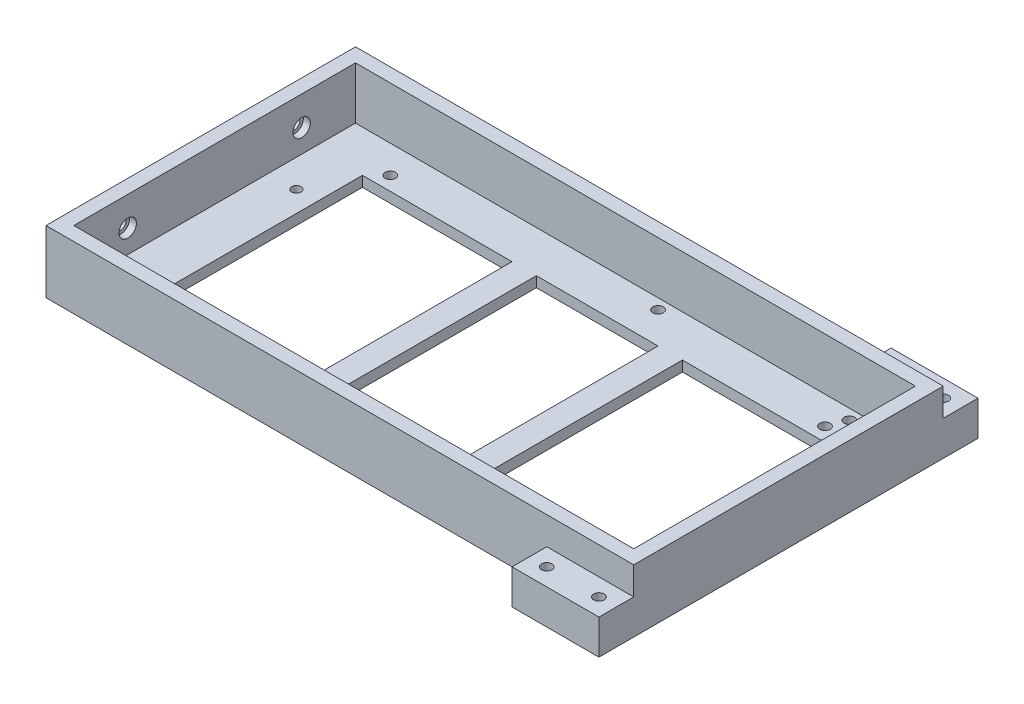
SolidWorks part; units mm, degrees
ref_plane "Front Plane" through (0, 0, 0) normal (0, 0, 1) x (1, 0, 0)
ref_plane "Top Plane" through (0, 0, 0) normal (0, 1, 0) x (1, 0, 0)
ref_plane "Right Plane" through (0, 0, 0) normal (1, 0, 0) x (0, 0, -1)
sketch "Sketch1" plane through (0, 0, 0) normal (0, 1, 0) x (1, 0, 0)
  line L1 (-80.5, -40.5) -> (80.5, -40.5)
  line L2 (-80.5, -40.5) -> (-80.5, 40.5)
  line L3 (-80.5, 40.5) -> (80.5, 40.5)
  line L4 (80.5, -40.5) -> (80.5, 40.5)
  line L5 (-80.5, -40.5) -> (80.5, 40.5) construction
  line L6 (-80.5, 40.5) -> (80.5, -40.5) construction
  line L7 (-84.5, -44.5) -> (84.5, -44.5)
  line L8 (-84.5, -44.5) -> (-84.5, 44.5)
  line L9 (-84.5, 44.5) -> (84.5, 44.5)
  line L10 (84.5, -44.5) -> (84.5, 44.5)
  line L11 (-84.5, -44.5) -> (84.5, 44.5) construction
  line L12 (-84.5, 44.5) -> (84.5, -44.5) construction
  point P0 (0, 0)
  point P6 (0, 0)
  dimension "D1" = 161
  dimension "D2" = 81
  dimension "D3" = 4
  dimension "D4" = 4
extrude "Boss-Extrude1" add sketch "Sketch1" along normal blind 15
sketch "Sketch2" plane through (0, 0, 0) normal (0, -1, 0) x (-1, 0, 0)
  line L0 (80.5, -40.5) -> (-80.5, -40.5) construction
  line L1 (84.5, 44.5) -> (-84.5, 44.5)
  line L2 (84.5, 44.5) -> (84.5, -44.5)
  line L3 (84.5, -44.5) -> (-84.5, -44.5)
  line L4 (-84.5, 44.5) -> (-84.5, -44.5)
  line L5 (84.5, 44.5) -> (-84.5, -44.5) construction
  line L6 (84.5, -44.5) -> (-84.5, 44.5) construction
  line L7 (66.5, 28.5) -> (23.5, 28.5)
  line L8 (66.5, 28.5) -> (66.5, -28.5)
  line L9 (66.5, -28.5) -> (23.5, -28.5)
  line L10 (-66.5, 28.5) -> (-66.5, -28.5)
  line L11 (66.5, 28.5) -> (-66.5, -28.5) construction
  line L12 (66.5, -28.5) -> (-66.5, 28.5) construction
  line L14 (-80.5, -40.5) -> (-80.5, 40.5) construction
  line L15 (-18.5, -28.5) -> (-18.5, 28.5)
  line L16 (-25.5, 28.5) -> (-25.5, -28.5)
  line L17 (-25.5, -28.5) -> (-66.5, -28.5)
  line L18 (-25.5, 28.5) -> (-66.5, 28.5)
  line L19 (16.5, 28.5) -> (16.5, -28.5)
  line L21 (23.5, -28.5) -> (23.5, 28.5)
  line L22 (16.5, 28.5) -> (-18.5, 28.5)
  line L23 (16.5, -28.5) -> (-18.5, -28.5)
  point P0 (0, 0)
  point P7 (0, 0)
  dimension "D1" = 12
  dimension "D2" = 14
  dimension "D3" = 55
  dimension "D4" = 7
  dimension "D5" = 50
  dimension "D6" = 7
extrude "Boss-Extrude2" add sketch "Sketch2" along normal blind 3
sketch "Sketch4" plane through (-80.5, 0, 0) normal (1, 0, 0) x (0, 0, -1)
  line L0 (-25, 6.6045) -> (25, 6.6045) construction
  circle A0 centre (-25, 6.6045) radius 1.5
  circle A1 centre (25, 6.6045) radius 1.5
  point P7 (0, 6.6045)
  dimension "D1" = 3
  dimension "D2" = 50
extrude "Cut-Extrude1" cut sketch "Sketch4" against normal blind 13
sketch "Sketch5" plane through (-80.5, 0, 0) normal (1, 0, 0) x (0, 0, -1)
  circle A0 centre (-25, 6.6045) radius 2.5
  circle A1 centre (25, 6.6045) radius 2.5
  dimension "D1" = 5
extrude "Cut-Extrude2" cut sketch "Sketch5" against normal blind 2
sketch "Sketch6" plane through (0, -3, 0) normal (0, -1, 0) x (-1, 0, 0)
  line L0 (-84.5, 44.5) -> (-84.5, -44.5) construction
  line L1 (66.5, -28.5) -> (66.5, -44.5) construction
  line L2 (-84.5, -44.5) -> (84.5, -44.5) construction
  line L3 (84.5, 44.5) -> (-84.5, 44.5) construction
  circle A0 centre (-9.5, 37.5) radius 1.5
  circle A1 centre (-64.5, 37.5) radius 1.5
  dimension "D1" = 3
  dimension "D2" = 55
  dimension "D3" = 20
  dimension "D4" = 7
extrude "Cut-Extrude3" cut sketch "Sketch6" against normal blind 10
sketch "Sketch8" plane through (0, 0, 0) normal (0, 1, 0) x (1, 0, 0)
  circle A0 centre (-62.5, 32.5) radius 1.5
  dimension "D1" = 3
  dimension "D2" = 62.5
  dimension "D3" = 32.5
extrude "Cut-Extrude4" cut sketch "Sketch8" against normal blind 4
mirror "Mirror1" about plane through (0, 0, 0) normal (1, 0, 0) of "Cut-Extrude4"
mirror "Mirror2" about plane through (0, 0, 0) normal (0, 0, 1) of "Mirror1", "Cut-Extrude4"
sketch "Sketch10" plane through (0, -3, 0) normal (0, -1, 0) x (1, 0, 0)
  circle A0 centre (72.5, 15.5) radius 1.35
  circle A1 centre (-72.5, -15.5) radius 1.35
  dimension "D1" = 2.7
  dimension "D2" = 72.5
  dimension "D3" = 15.5
  dimension "D4" = 72.5
  dimension "D5" = 15.5
extrude "Cut-Extrude5" cut sketch "Sketch10" against normal blind 4
sketch "Sketch11" plane through (0, -3, 0) normal (0, -1, 0) x (1, 0, 0)
  line L0 (84.5, 44.5) -> (-84.5, 44.5) construction
  line L1 (59.5, 44.5) -> (84.5, 44.5)
  line L2 (59.5, 44.5) -> (59.5, 54.5)
  line L3 (59.5, 54.5) -> (84.5, 54.5)
  line L4 (84.5, 44.5) -> (84.5, 54.5)
  line L7 (84.5, -44.5) -> (84.5, 44.5) construction
  point P6 (0, 0)
  dimension "D1" = 25
  dimension "D2" = 10
extrude "Boss-Extrude3" add sketch "Sketch11" against normal blind 10
sketch "Sketch12" plane through (0, -3, 0) normal (0, -1, 0) x (1, 0, 0)
  line L0 (84.5, 54.5) -> (59.5, 54.5) construction
  line L1 (84.5, -44.5) -> (84.5, 54.5) construction
  line L2 (64.5, 49.5) -> (79.5, 49.5) construction
  circle A0 centre (64.5, 49.5) radius 1.5
  circle A1 centre (79.5, 49.5) radius 1.5
  point P7 (72, 54.5)
  point P10 (72, 49.5)
  dimension "D2" = 3
  dimension "D3" = 3
  dimension "D1" = 5
  dimension "D5" = 5
extrude "Cut-Extrude6" cut sketch "Sketch12" against normal blind 10
mirror "Mirror3" about plane through (0, 0, 0) normal (0, 0, 1) of "Boss-Extrude3", "Cut-Extrude6"
